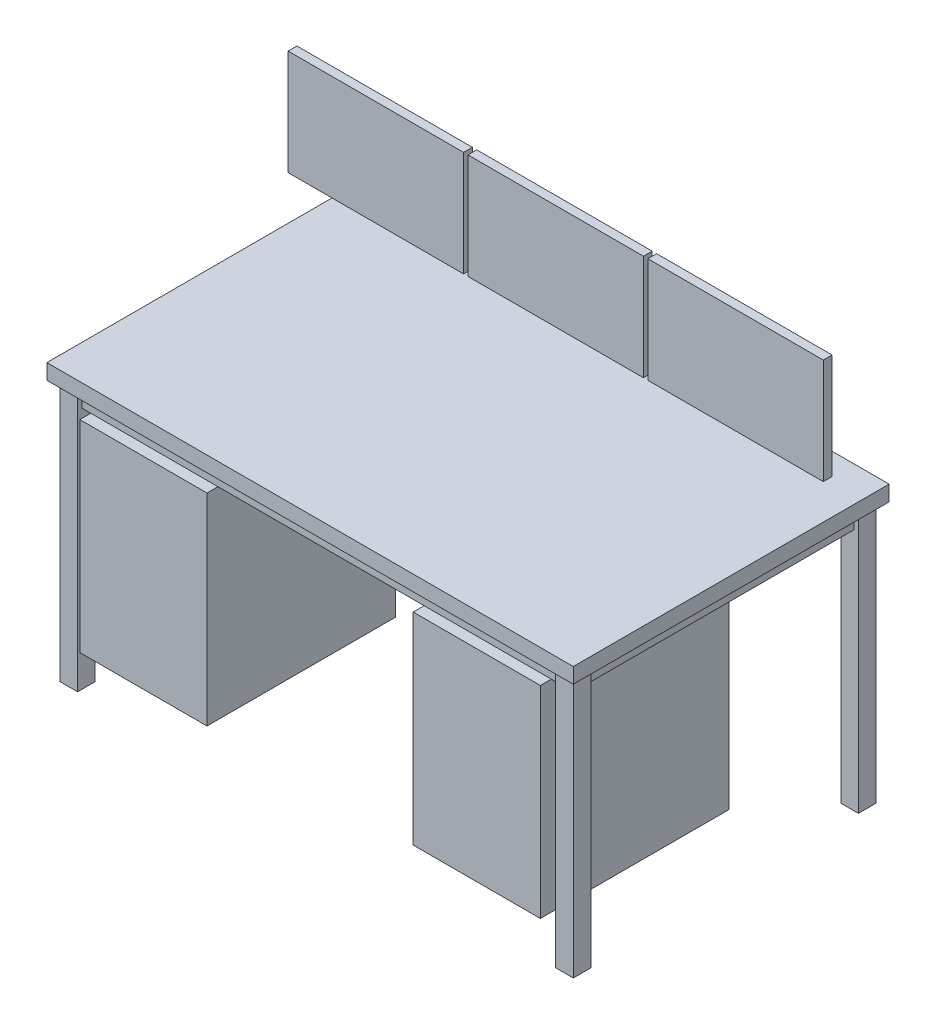
SolidWorks part; units mm, degrees
material "Plain Carbon Steel"
ref_plane "Front Plane" through (0, 0, 0) normal (0, 0, 1) x (1, 0, 0)
ref_plane "Top Plane" through (0, 0, 0) normal (0, 1, 0) x (1, 0, 0)
ref_plane "Right Plane" through (0, 0, 0) normal (1, 0, 0) x (0, 0, -1)
sketch "Sketch1" plane through (0, 0, 0) normal (0, 1, 0) x (1, 0, 0)
  line L1 (-762, -457.2) -> (762, -457.2)
  line L2 (-762, -457.2) -> (-762, 457.2)
  line L3 (-762, 457.2) -> (762, 457.2)
  line L4 (762, -457.2) -> (762, 457.2)
  line L5 (-762, -457.2) -> (762, 457.2) construction
  line L6 (-762, 457.2) -> (762, -457.2) construction
  point P0 (0, 0)
  dimension "D1" = 1524
  dimension "D2" = 914.4
extrude "Boss-Extrude1" add sketch "Sketch1" against normal blind 44.45
sketch "Sketch2" plane through (0, -44.45, 0) normal (0, -1, 0) x (1, 0, 0)
  line L0 (-762, 457.2) -> (762, 457.2) construction
  line L1 (742.95, 438.15) -> (692.15, 438.15)
  line L2 (742.95, 438.15) -> (742.95, 387.35)
  line L3 (742.95, 387.35) -> (692.15, 387.35)
  line L4 (692.15, 438.15) -> (692.15, 387.35)
  line L5 (742.95, -438.15) -> (692.15, -438.15)
  line L6 (742.95, -438.15) -> (742.95, -387.35)
  line L7 (742.95, -387.35) -> (692.15, -387.35)
  line L8 (692.15, -438.15) -> (692.15, -387.35)
  line L9 (-742.95, -438.15) -> (-692.15, -438.15)
  line L10 (-742.95, -438.15) -> (-742.95, -387.35)
  line L11 (-742.95, -387.35) -> (-692.15, -387.35)
  line L12 (-692.15, -438.15) -> (-692.15, -387.35)
  line L13 (-742.95, 438.15) -> (-692.15, 438.15)
  line L14 (-742.95, 438.15) -> (-742.95, 387.35)
  line L15 (-742.95, 387.35) -> (-692.15, 387.35)
  line L16 (-692.15, 438.15) -> (-692.15, 387.35)
  line L17 (762, 457.2) -> (762, -457.2) construction
  line L18 (762, -457.2) -> (-762, -457.2) construction
  line L19 (-762, -457.2) -> (-762, 457.2) construction
  dimension "D1" = 50.8
  dimension "D2" = 19.05
  dimension "D3" = 19.05
  dimension "D4" = 19.05
  dimension "D5" = 19.05
extrude "Boss-Extrude2" add sketch "Sketch2" along normal offset from surface (755.65 mm away) 800.1 up to face at (0, 0, 0)
sketch "Sketch3" plane through (0, -44.45, 0) normal (0, -1, 0) x (1, 0, 0)
  line L0 (-762, 457.2) -> (762, 457.2) construction
  line L5 (-730.25, -425.45) -> (730.25, -425.45)
  line L6 (-730.25, -425.45) -> (-730.25, 425.45)
  line L7 (-730.25, 425.45) -> (730.25, 425.45)
  line L8 (730.25, -425.45) -> (730.25, 425.45)
  line L9 (-730.25, -425.45) -> (730.25, 425.45) construction
  line L10 (-730.25, 425.45) -> (730.25, -425.45) construction
  line L11 (762, 457.2) -> (762, -457.2) construction
  line L12 (-704.85, -400.05) -> (-704.85, 400.05)
  line L13 (-704.85, 400.05) -> (704.85, 400.05)
  line L14 (704.85, -400.05) -> (704.85, 400.05)
  line L15 (-704.85, -400.05) -> (704.85, -400.05)
  point P0 (0, 0)
  dimension "D1" = 31.75
  dimension "D2" = 31.75
  dimension "D3" = 25.4
extrude "Boss-Extrude3" add sketch "Sketch3" along normal blind 50.8
sketch "Sketch4" plane through (0, -95.25, 0) normal (0, -1, 0) x (1, 0, 0)
  line L0 (-762, 457.2) -> (762, 457.2) construction
  line L1 (-666.75, -88.9) -> (-298.45, -88.9)
  line L2 (-666.75, -88.9) -> (-666.75, 457.2)
  line L3 (-666.75, 457.2) -> (-298.45, 457.2)
  line L4 (-298.45, -88.9) -> (-298.45, 457.2)
  line L5 (666.75, -88.9) -> (298.45, -88.9)
  line L6 (666.75, -88.9) -> (666.75, 457.2)
  line L7 (666.75, 457.2) -> (298.45, 457.2)
  line L8 (298.45, -88.9) -> (298.45, 457.2)
  line L9 (692.15, 438.15) -> (692.15, 425.45) construction
  line L10 (-692.15, 425.45) -> (-692.15, 438.15) construction
  dimension "D1" = 25.4
  dimension "D2" = 25.4
  dimension "D3" = 368.3
  dimension "D4" = 546.1
extrude "Boss-Extrude4" add sketch "Sketch4" along normal blind 584.2
ref_plane "Plane1" through (0, 0, -254) normal (0, 0, 1) x (1, 0, 0)
sketch "Sketch5" plane through (0, 0, -254) normal (0, 0, 1) x (1, 0, 0)
  line L0 (0, 199.9341) -> (0, 490.6797) construction
  line L1 (762, 0) -> (-762, 0) construction
  line L2 (-774.7, 419.1) -> (-266.7, 419.1)
  line L3 (-774.7, 419.1) -> (-774.7, 114.3)
  line L4 (-774.7, 114.3) -> (-266.7, 114.3)
  line L5 (-266.7, 419.1) -> (-266.7, 114.3)
  line L6 (-254, 419.1) -> (254, 419.1)
  line L7 (-254, 419.1) -> (-254, 114.3)
  line L8 (-254, 114.3) -> (254, 114.3)
  line L9 (254, 419.1) -> (254, 114.3)
  line L10 (266.7, 419.1) -> (774.7, 419.1)
  line L11 (266.7, 419.1) -> (266.7, 114.3)
  line L12 (266.7, 114.3) -> (774.7, 114.3)
  line L13 (774.7, 419.1) -> (774.7, 114.3)
  dimension "D1" = 304.8
  dimension "D2" = 508
  dimension "D3" = 12.7
  dimension "D4" = 114.3
extrude "Boss-Extrude5" add sketch "Sketch5" against normal blind 25.4 separate body
